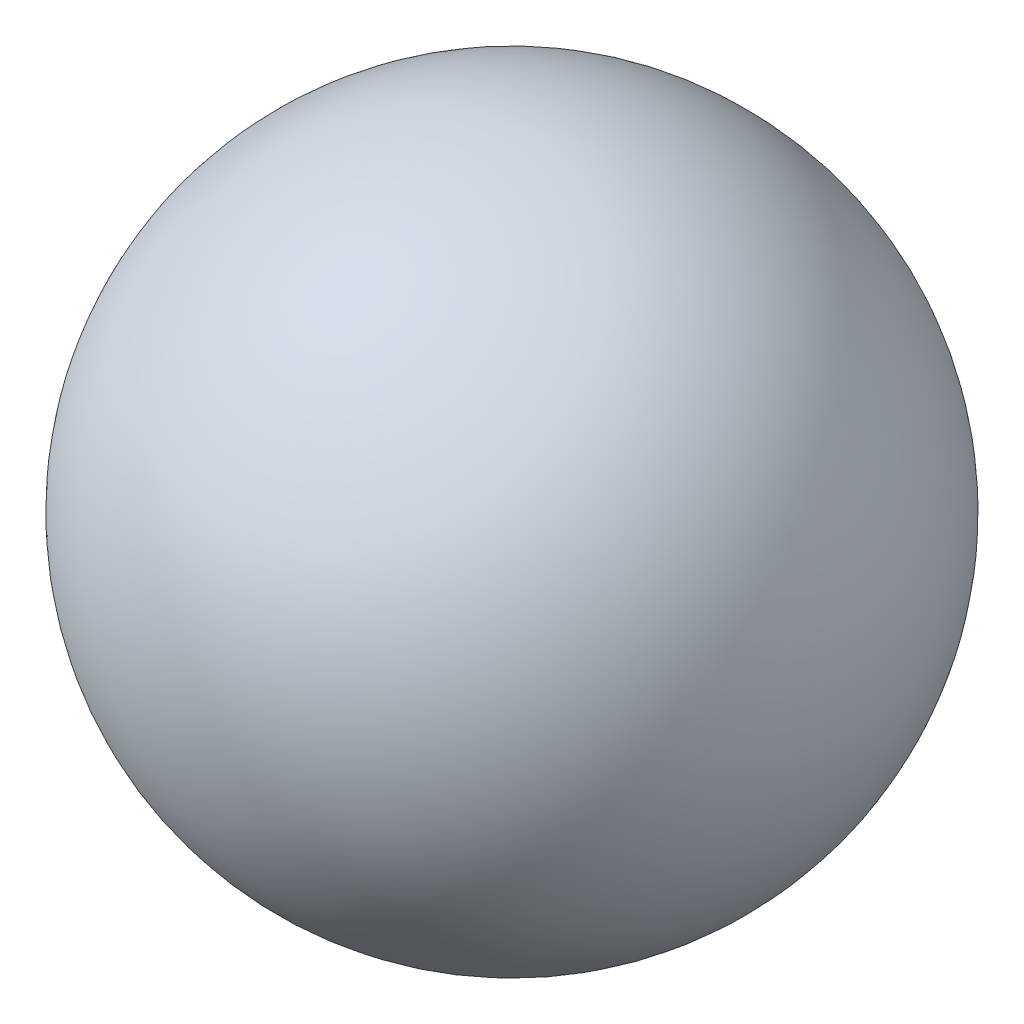
SolidWorks part; units mm, degrees
ref_plane "Front Plane" through (0, 0, 0) normal (0, 0, 1) x (1, 0, 0)
ref_plane "Top Plane" through (0, 0, 0) normal (0, 1, 0) x (1, 0, 0)
ref_plane "Right Plane" through (0, 0, 0) normal (1, 0, 0) x (0, 0, -1)
sketch "Sketch1" plane through (0, 0, 0) normal (0, 0, 1) x (1, 0, 0)
  line L0 (0, 0) -> (25000, 0) construction
  line L1 (-3.6923, 0) -> (3.6923, 0)
  arc A0 (-3.6923, 0) -> (3.6923, 0) centre (0, 0) ccw
  dimension "D1" = 7.3846
revolve "Revolve1" add sketch "Sketch1" angle 360 about L0
